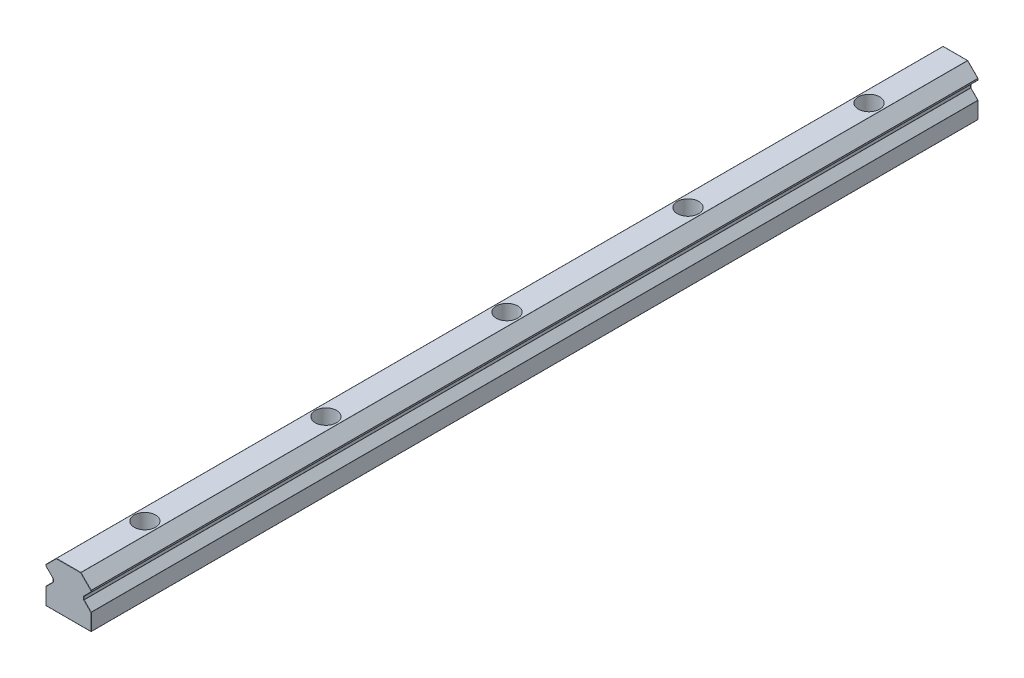
SolidWorks part; units mm, degrees
material "Кованая нержавеющая сталь"
ref_plane "Спереди" through (0, 0, 0) normal (0, 0, 1) x (1, 0, 0)
ref_plane "Сверху" through (0, 0, 0) normal (0, 1, 0) x (1, 0, 0)
ref_plane "Справа" through (0, 0, 0) normal (1, 0, 0) x (0, 0, -1)
sketch "Эскиз1" plane through (0, 0, 0) normal (0, 0, 1) x (1, 0, 0)
  line L0 (-8.0778, -6.7525) -> (6.9222, -6.7525)
  line L1 (6.9222, -6.7525) -> (6.9222, -1.1525)
  line L2 (6.9222, -1.1525) -> (4.5384, 1.2313)
  line L3 (4.5384, 1.2313) -> (4.5384, 2.2341)
  line L4 (4.5384, 2.2341) -> (6.9222, 4.6179)
  line L5 (6.9222, 4.6179) -> (6.9222, 5.1179)
  line L6 (6.9222, 5.1179) -> (3.4925, 8.5475)
  line L7 (3.4925, 8.5475) -> (-4.6481, 8.5475)
  line L8 (-4.6481, 8.5475) -> (-8.0778, 5.1179)
  line L9 (-8.0778, 5.1179) -> (-8.0778, 4.6179)
  line L10 (-8.0778, 4.6179) -> (-5.694, 2.2341)
  line L11 (-5.694, 2.2341) -> (-5.694, 1.2313)
  line L12 (-5.694, 1.2313) -> (-8.0778, -1.1525)
  line L13 (-8.0778, -1.1525) -> (-8.0778, -6.7525)
  dimension "D1" = 15
  dimension "D2" = 15.3
  dimension "D3" = 135
  dimension "D4" = 135
  dimension "D5" = 15
  dimension "D6" = 0.5
  dimension "D7" = 5.6
  dimension "D8" = 135
  dimension "D9" = 135
extrude "Бобышка-Вытянуть1" add sketch "Эскиз1" along normal blind 294
fillet "Скругление1" radius 0.1 42 edges at (6.9222, 4.6179, 147) (5.7303, 3.426, 0) (6.9222, 4.8679, 0) (-0.5778, -6.7525, 0) (-8.0778, -6.7525, 147) (-8.0778, -3.9525, 0) (-8.0778, -1.1525, 147) (-6.8859, 0.0394, 0) (-5.694, 1.2313, 147) (-5.694, 1.7327, 0) (-8.0778, 4.8679, 0) (-8.0778, 4.6179, 147) (-5.694, 2.2341, 147) (-6.8859, 3.426, 0) (-8.0778, 5.1179, 147) (-6.363, 6.8327, 0) (4.5384, 2.2341, 147) (4.5384, 1.7327, 0) (6.9222, -6.7525, 147) (6.9222, -3.9525, 0) (6.9222, -1.1525, 147) (4.5384, 1.2313, 147) (5.7303, 0.0394, 0) (6.9222, 5.1179, 147) (5.2073, 6.8327, 0) (-6.8859, 0.0394, 294) (-5.694, 1.7327, 294) (-6.8859, 3.426, 294) (-8.0778, 4.8679, 294) (-6.363, 6.8327, 294) (5.2073, 6.8327, 294) (6.9222, 4.8679, 294) (5.7303, 3.426, 294) (4.5384, 1.7327, 294) (5.7303, 0.0394, 294) (6.9222, -3.9525, 294) (-0.5778, -6.7525, 294) (-8.0778, -3.9525, 294) (3.4925, 8.5475, 147) (-0.5778, 8.5475, 294) (-4.6481, 8.5475, 147) (-0.5778, 8.5475, 0)
sketch "Эскиз2" plane through (0, 8.5475, 0) normal (0, 1, 0) x (1, 0, 0)
  line L0 (-4.6774, -293.9) -> (-4.6774, -0.1) construction
  line L1 (3.4511, -0.1) -> (-4.6067, -0.1) construction
  circle A0 centre (-0.6474, -28.6) radius 3.55
  dimension "D1" = 4.03
  dimension "D2" = 28.5
extrude "Вырез-Вытянуть1" cut sketch "Эскиз2" against normal blind 6
pattern_linear "Линейный массив1" count 20 spacing 60 along (0, 0, 1) of "Вырез-Вытянуть1"
sketch "Эскиз3" plane through (0, 2.5475, 0) normal (0, 1, 0) x (1, 0, 0)
  circle A0 centre (-0.6474, -28.6) radius 2.25
extrude "Вырез-Вытянуть3" cut sketch "Эскиз3" against normal blind 20
pattern_linear "Линейный массив2" count 20 spacing 60 along (0, 0, 1) of "Вырез-Вытянуть3"
